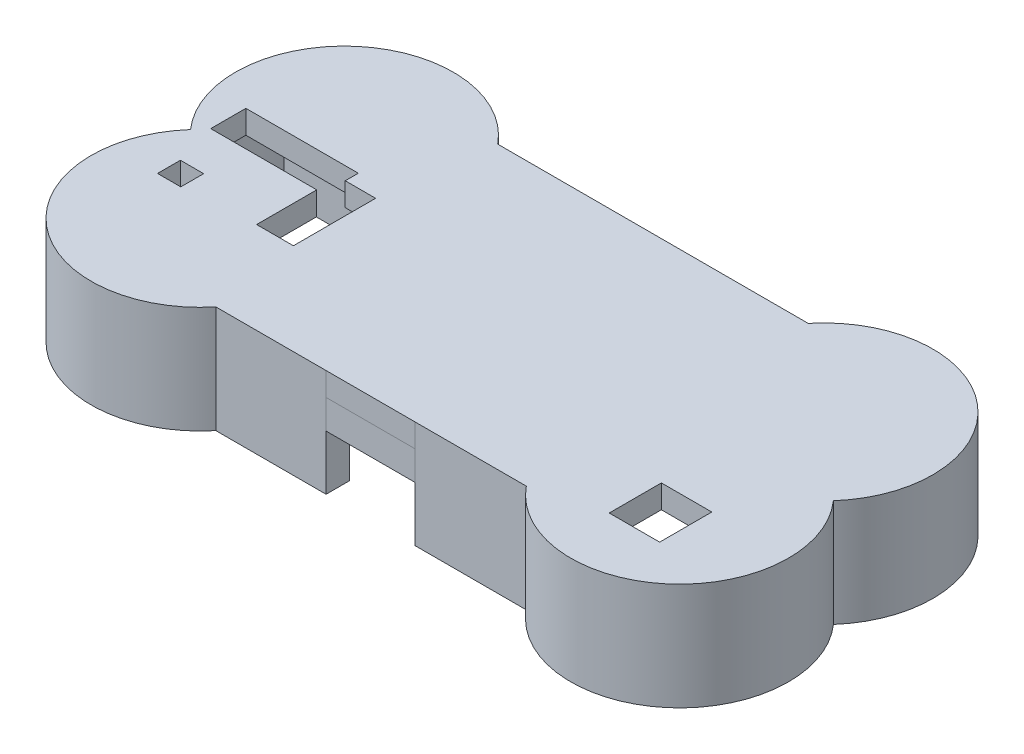
SolidWorks part; units mm, degrees
material "ABS PC"
ref_plane "Front Plane" through (0, 0, 0) normal (0, 0, 1) x (1, 0, 0)
ref_plane "Top Plane" through (0, 0, 0) normal (0, 1, 0) x (1, 0, 0)
ref_plane "Right Plane" through (0, 0, 0) normal (1, 0, 0) x (0, 0, -1)
sketch "Sketch2" plane through (0, 0, 0) normal (0, 1, 0) x (1, 0, 0)
  line L0 (19.9652, 14.9922) -> (-16.4848, 14.9912)
  line L1 (-16.4838, -10.6618) -> (19.9662, -10.6608)
  line L2 (21.2428, -11.1796) -> (29.4142, -11.1796)
  line L3 (29.4142, -11.1796) -> (29.4142, -6.5996)
  line L5 (-24.8141, -11.1676) -> (-24.8141, -6.4176)
  line L7 (-29.7232, 2.1554) -> (-29.7232, 7.185)
  line L8 (-16.7252, 5.7616) -> (-20.7333, 5.7616)
  line L9 (-16.7252, 5.7616) -> (-16.7252, -3.2021)
  line L10 (-16.7252, -3.2021) -> (-20.7333, -3.2021)
  line L11 (-20.7333, 5.7616) -> (-20.7333, -3.2021)
  line L12 (-16.7252, -7.6492) -> (23.6085, -7.6492)
  line L13 (-16.7252, -7.6492) -> (-16.7252, 11.6804)
  line L14 (-16.7252, 11.6804) -> (23.6085, 11.6804)
  line L15 (23.6085, -7.6492) -> (23.6085, 11.6804)
  line L16 (-29.7232, 7.185) -> (-32.7724, 7.185)
  line L17 (-32.7724, 7.185) -> (-20.7333, 7.185)
  line L18 (-20.7333, 7.185) -> (-20.7333, 5.7616)
  line L19 (-15.1846, -13.2017) -> (18.6669, -13.2008)
  line L20 (18.666, 17.5322) -> (-15.1856, 17.5313)
  line L21 (6.5265, -10.6611) -> (6.5265, -13.2011)
  line L22 (-3.1615, -10.6614) -> (-3.1615, -13.2014)
  arc A0 (-16.4848, 14.9912) -> (-29.4378, 2.1652) centre (-24.4004, 10.0316) ccw
  arc A1 (-29.4378, 2.1652) -> (-16.4838, -10.6618) centre (-24.3995, -5.7012) ccw
  arc A2 (19.9662, -10.6608) -> (32.9192, 2.1652) centre (27.8818, -5.7011) ccw
  arc A3 (32.9192, 2.1652) -> (19.9652, 14.9922) centre (27.8809, 10.0317) ccw
  circle A4 centre (-24.8048, -8.151) radius 1.7334
  circle A5 centre (29.4142, -8.3354) radius 1.7334
  circle A6 centre (-2.4122, -8.3504) radius 0.7493
  circle A7 centre (5.7772, -8.3758) radius 0.7493
  circle A8 centre (-27.0565, 5.2004) radius 0.0119
  circle A9 centre (-27.4058, 5.0862) radius 0.3556
  circle A10 centre (-25.5008, 5.0862) radius 0.3556
  circle A11 centre (-21.3098, 5.8482) radius 0.3576
  circle A12 centre (-29.6918, -2.5338) radius 0.3556
  arc A13 (-15.1856, 17.5313) -> (-33.3042, 2.1651) centre (-24.4004, 10.0316) ccw
  arc A14 (-33.3042, 2.1651) -> (-15.1846, -13.2017) centre (-24.3995, -5.7012) ccw
  arc A15 (18.6669, -13.2008) -> (36.7856, 2.1654) centre (27.8818, -5.7011) ccw
  arc A16 (36.7856, 2.1654) -> (18.666, 17.5322) centre (27.8809, 10.0317) ccw
  dimension "D1" = 2.54
extrude "Boss-Extrude1" add sketch "Sketch2" against normal blind 9.144
sketch "Sketch3" plane through (0, 0, 0) normal (0, 1, 0) x (-1, 0, 0)
  line L3 (20.7333, 3.2021) -> (16.7252, 3.2021)
  line L4 (-19.9662, 10.6608) -> (-6.5265, 10.6611)
  line L5 (-18.666, -17.5322) -> (15.1856, -17.5313)
  line L7 (-18.666, -17.5322) -> (15.1856, -17.5313)
  line L8 (20.7333, 3.2021) -> (20.7333, -5.7616)
  line L9 (20.7333, -5.7616) -> (16.7252, -5.7616)
  line L10 (16.7252, 3.2021) -> (16.7252, -5.7616)
  line L15 (28.4231, 3.781) -> (30.9606, 3.781)
  line L16 (28.4231, 3.781) -> (28.4231, 1.2865)
  line L21 (-25.724, 5.5327) -> (-31.222, 5.5327)
  line L22 (-25.724, 5.5327) -> (-25.724, 11.2193)
  line L23 (28.4231, 1.2865) -> (30.9606, 1.2865)
  line L24 (30.9606, 3.781) -> (30.9606, 1.2865)
  line L25 (28.4231, 3.781) -> (30.9606, 1.2865) construction
  line L26 (28.4231, 1.2865) -> (30.9606, 3.781) construction
  line L43 (-6.5265, 10.6611) -> (3.1615, 10.6611)
  line L44 (-6.5265, 10.6611) -> (-6.5265, 13.2014)
  line L45 (-6.5265, 13.2014) -> (3.1615, 13.2014)
  line L46 (3.1615, 10.6611) -> (3.1615, 13.2014)
  line L47 (20.0371, -7.185) -> (32.2925, -7.185)
  line L48 (20.0371, -7.185) -> (20.0371, -3.3507)
  line L50 (20.0371, -3.3507) -> (32.2925, -3.3507)
  line L52 (-19.9662, 10.6608) -> (-6.5265, 10.6611)
  line L54 (3.1615, 13.2014) -> (3.1615, 10.6614)
  line L55 (3.1615, 13.2014) -> (3.1615, 10.6614)
  line L56 (-6.5265, 13.2011) -> (-18.6669, 13.2008)
  line L58 (-6.5265, 10.6611) -> (-6.5265, 13.2011)
  line L59 (-6.5265, 10.6611) -> (-6.5265, 13.2011)
  line L60 (-6.5265, 13.2011) -> (-18.6669, 13.2008)
  line L62 (16.4848, -14.9912) -> (-19.9652, -14.9922)
  line L63 (16.4848, -14.9912) -> (-19.9652, -14.9922)
  line L64 (15.1846, 13.2017) -> (3.1615, 13.2014)
  line L65 (15.1846, 13.2017) -> (3.1615, 13.2014)
  line L66 (3.1615, 10.6614) -> (16.4838, 10.6618)
  line L67 (3.1615, 10.6614) -> (16.4838, 10.6618)
  line L68 (32.2925, -7.185) -> (32.2925, -3.3507)
  line L69 (-25.724, 11.2193) -> (-31.222, 11.2193)
  line L70 (-31.222, 5.5327) -> (-31.222, 11.2193)
  line L71 (-25.724, 5.5327) -> (-31.222, 11.2193) construction
  line L72 (-25.724, 11.2193) -> (-31.222, 5.5327) construction
  arc A6 (-18.6669, 13.2008) -> (-36.7856, -2.1654) centre (-27.8818, 5.7011) ccw
  arc A7 (33.3042, -2.1651) -> (15.1846, 13.2017) centre (24.3995, 5.7012) ccw
  arc A8 (15.1856, -17.5313) -> (33.3042, -2.1651) centre (24.4004, -10.0316) ccw
  arc A9 (-36.7856, -2.1654) -> (-18.666, -17.5322) centre (-27.8809, -10.0317) ccw
  arc A10 (-18.6669, 13.2008) -> (-36.7856, -2.1654) centre (-27.8818, 5.7011) ccw
  arc A11 (33.3042, -2.1651) -> (15.1846, 13.2017) centre (24.3995, 5.7012) ccw
  arc A12 (15.1856, -17.5313) -> (33.3042, -2.1651) centre (24.4004, -10.0316) ccw
  arc A13 (-36.7856, -2.1654) -> (-18.666, -17.5322) centre (-27.8809, -10.0317) ccw
  arc A19 (16.4848, -14.9912) -> (29.4378, -2.1652) centre (24.4004, -10.0316) ccw
  arc A20 (16.4848, -14.9912) -> (29.4378, -2.1652) centre (24.4004, -10.0316) ccw
  arc A21 (29.4378, -2.1652) -> (16.4838, 10.6618) centre (24.3995, 5.7012) ccw
  arc A22 (29.4378, -2.1652) -> (16.4838, 10.6618) centre (24.3995, 5.7012) ccw
  arc A25 (-19.9662, 10.6608) -> (-32.9192, -2.1652) centre (-27.8818, 5.7011) ccw
  arc A26 (-19.9662, 10.6608) -> (-32.9192, -2.1652) centre (-27.8818, 5.7011) ccw
  arc A27 (-32.9192, -2.1652) -> (-19.9652, -14.9922) centre (-27.8809, -10.0317) ccw
  arc A28 (-32.9192, -2.1652) -> (-19.9652, -14.9922) centre (-27.8809, -10.0317) ccw
  point P14 (24.8048, 8.151)
  point P15 (29.6918, 2.5338)
  point P19 (-28.473, 8.376)
  dimension "D1" = 0
extrude "Boss-Extrude7" add sketch "Sketch3" along normal blind 2.54
sketch "Sketch8" plane through (0, 0, 0) normal (0, -1, 0) x (1, 0, 0)
  line L0 (19.9652, -14.9922) -> (19.9652, -12.4522)
  line L1 (19.9652, -12.4522) -> (36.9034, -12.4522)
  line L2 (36.9034, -12.4522) -> (-33.4224, -12.4522)
  line L3 (32.9192, -2.1652) -> (26.6769, -2.1652)
  line L4 (26.6769, -2.1652) -> (26.6769, -12.4522)
  line L5 (19.9662, 10.6608) -> (19.9662, 8.1373)
  line L6 (19.9662, 8.1373) -> (7.4176, 8.1373)
  line L7 (7.4176, 8.1373) -> (7.4176, 10.6611)
  line L8 (-16.4838, 10.6618) -> (19.9662, 10.6608) construction
  line L9 (7.4176, 10.6611) -> (19.9662, 10.6608)
  arc A0 (19.9652, -14.9922) -> (32.9192, -2.1652) centre (27.8809, -10.0317) ccw construction
  arc A1 (-29.4378, -2.1652) -> (-16.4848, -14.9912) centre (-24.4004, -10.0316) ccw construction
  arc M2 (-32.2925, -5.0346) -> (-16.4848, -14.9912) centre (-24.4004, -10.0316) ccw
  line M3 (-16.4848, -14.9912) -> (19.9652, -14.9922)
  arc M4 (19.9652, -14.9922) -> (32.9192, -2.1652) centre (27.8809, -10.0317) ccw
  line M6 (19.9662, 10.6608) -> (6.5265, 10.6611)
  dimension "D1" = 2.54
extrude "Boss-Extrude8" add sketch "Sketch8" along normal blind 9.144 contours L0 L2 M2 M3 | L1 L0 L2 M4 | L3 L4 L2 M4 | L7 L6 L5 M6
sketch "Sketch9" plane through (0, 0, 0) normal (0, -1, 0) x (1, 0, 0)
  line L1 (6.5265, 13.2012) -> (-3.1615, 13.2012)
  line L2 (6.5265, 13.2012) -> (6.5265, 10.6614)
  line L3 (6.5265, 10.6614) -> (-3.1615, 10.6614)
  line L4 (-3.1615, 13.2012) -> (-3.1615, 10.6614)
extrude "Boss-Extrude9" add sketch "Sketch9" along normal blind 3.175
